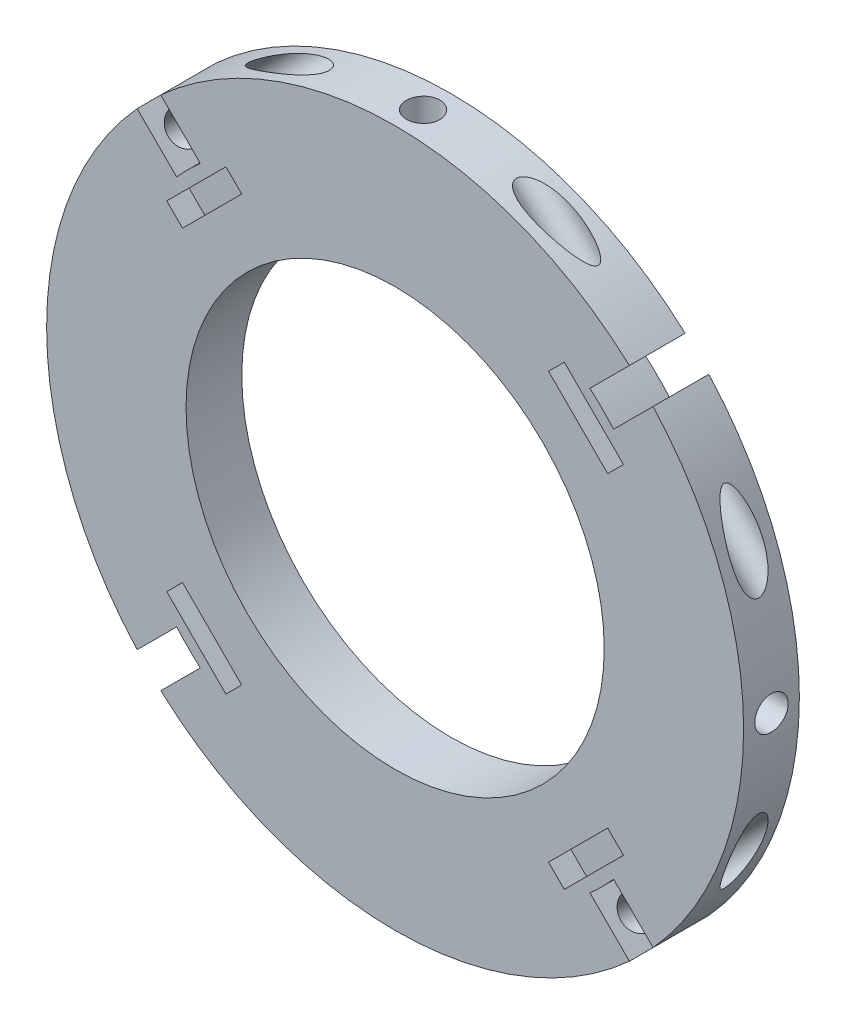
SolidWorks part; units mm, degrees
ref_plane "Ön Düzlem" through (0, 0, 0) normal (0, 0, 1) x (1, 0, 0)
ref_plane "Üst Düzlem" through (0, 0, 0) normal (0, 1, 0) x (1, 0, 0)
ref_plane "Sağ Düzlem" through (0, 0, 0) normal (1, 0, 0) x (0, 0, -1)
sketch "Sketch1" plane through (0, 0, 0) normal (0, 0, 1) x (1, 0, 0)
  circle A0 centre (0, 0) radius 62.5
  circle A1 centre (0, 0) radius 37.5
extrude "Boss-Extrude1" add sketch "Sketch1" along normal mid plane 10
sketch "Sketch2" plane through (0, 0, 5) normal (0, 0, 1) x (1, 0, 0)
  line L0 (0, 0) -> (0, 62.5) construction
  line L1 (0, 0) -> (44.1942, 44.1942) construction
  line L2 (42.0219, 46.2646) -> (34.9411, 39.1838)
  line L3 (46.2646, 42.0219) -> (39.1838, 34.9411)
  circle A0 centre (0, 0) radius 62.5 construction
  circle A3 centre (0, 0) radius 62.5
  circle A4 centre (0, 0) radius 52.5
  point P13 (0, 0)
  circle M3 centre (0, 0) radius 62.5
  dimension "D4" = 10
  dimension "D5" = 125
  dimension "D1" = 45
  dimension "D2" = 3
  dimension "D3" = 6
extrude "Kanat Bölmesi" cut sketch "Sketch2" against normal up to surface (10 mm away) contours A4 L3 L2 M3
sketch "Sketch3" plane through (-2.1213, 2.1213, 0) normal (0.7071, -0.7071, 0) x (0, 0, -1)
  line L0 (5, 62.428) -> (5, 52.428) construction
  line L1 (5, 52.4142) -> (5, 62.428) construction
  line L2 (-5, 62.428) -> (-5, 52.428) construction
  line L3 (-5, 62.428) -> (-5, 52.4142) construction
  line L4 (-5, 57.428) -> (5, 57.428) construction
  circle A0 centre (0, 57.428) radius 3
  dimension "D1" = 6
extrude "Kanat Tutucu Deliği" cut sketch "Sketch3" against normal mid plane 109
sketch "Sketch4" plane through (0, 0, 0) normal (0, 1, 0) x (1, 0, 0)
  circle A0 centre (0, 0) radius 3
extrude "Merkezleme Deliği" cut sketch "Sketch4" along normal blind 8 from offset 55
pattern_circular "MD Ayna" count 4 over 360 about axis through (0, 0, 0) along (0, 0, 1) of "Merkezleme Deliği"
pattern_circular "KB Ayna" count 4 over 360 about axis through (0, 0, 0) along (0, 0, 1) of "Kanat Bölmesi", "Kanat Tutucu Deliği"
sketch "Sketch5" plane through (0, 0, 5) normal (0, 0, 1) x (1, 0, 0)
  line L0 (0, 0) -> (44.1942, 44.1942) construction
  line L1 (34.601, 52.0483) -> (21.5092, 38.9565)
  line L2 (51.7927, 34.9824) -> (38.7281, 21.9178)
  line L3 (42.0219, 46.2646) -> (34.9411, 39.1838)
  line L4 (34.9411, 39.1838) -> (39.1838, 34.9411)
  line L5 (39.1838, 34.9411) -> (46.2646, 42.0219)
  line L6 (0, 0) -> (0, 62.5) construction
  line L7 (30.3449, 40.9515) -> (27.5165, 38.1231)
  line L8 (27.5165, 38.1231) -> (38.1231, 27.5165)
  line L9 (38.1231, 27.5165) -> (40.9515, 30.3449)
  line L10 (40.9515, 30.3449) -> (30.3449, 40.9515)
  line L11 (34.9411, 39.1838) -> (28.3388, 45.7861) construction
  circle A0 centre (0, 0) radius 62.5
  circle A1 centre (0, 0) radius 44.5
  point P22 (35.6482, 35.6482)
  dimension "D1" = 125
  dimension "D2" = 89
  dimension "D3" = 45
  dimension "D4" = 4
  dimension "D5" = 15
  dimension "D6" = 4
extrude "Cut-Extrude4" cut sketch "Sketch5" against normal blind 4 contours L9 L10 L7 L8
pattern_circular "CirPattern4" count 4 over 360 about axis through (0, 0, 0) along (0, 0, 1) of "Cut-Extrude4"
